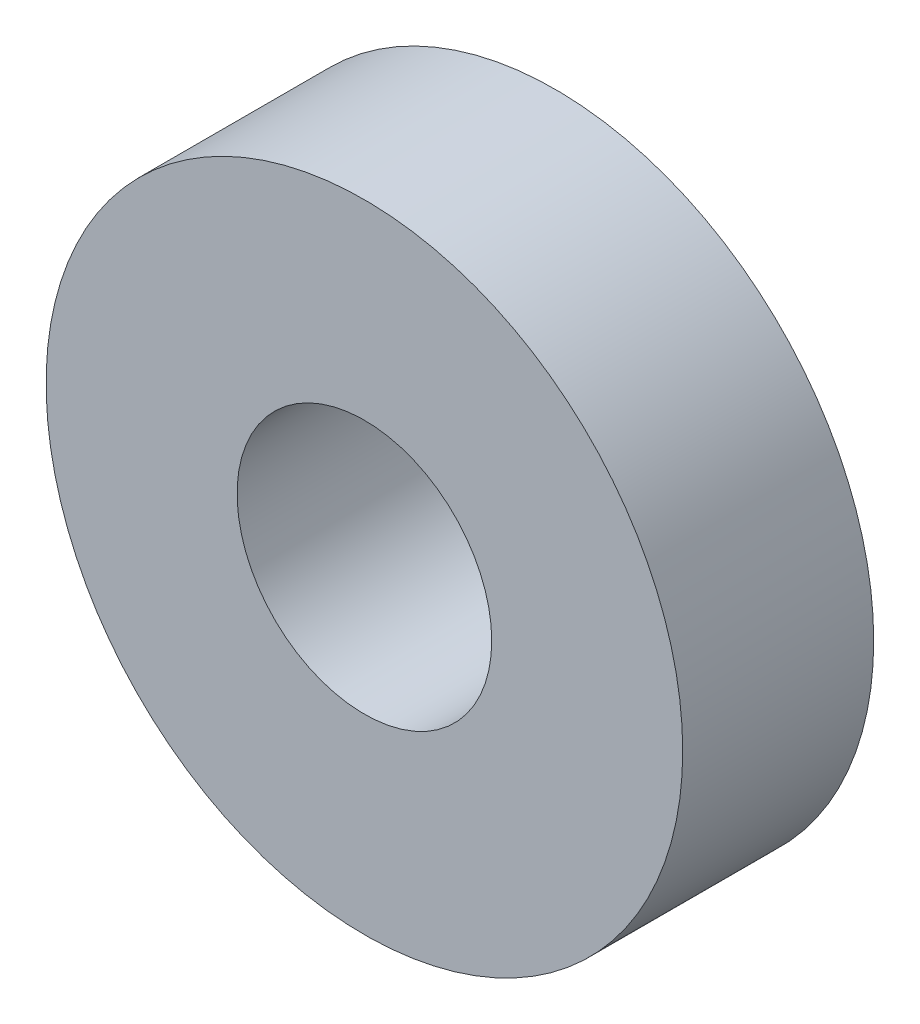
SolidWorks part; units mm, degrees
material "AISI 304"
ref_plane "前视基准面" through (0, 0, 0) normal (0, 0, 1) x (1, 0, 0)
ref_plane "上视基准面" through (0, 0, 0) normal (0, 1, 0) x (1, 0, 0)
ref_plane "右视基准面" through (0, 0, 0) normal (1, 0, 0) x (0, 0, -1)
sketch "草图1" plane through (0, 0, 0) normal (0, 0, 1) x (1, 0, 0)
  circle A0 centre (0, 0) radius 2.5
  circle A1 centre (0, 0) radius 1
  dimension "D1" = 5
  dimension "D2" = 2
extrude "凸台-拉伸1" add sketch "草图1" along normal blind 1.5
